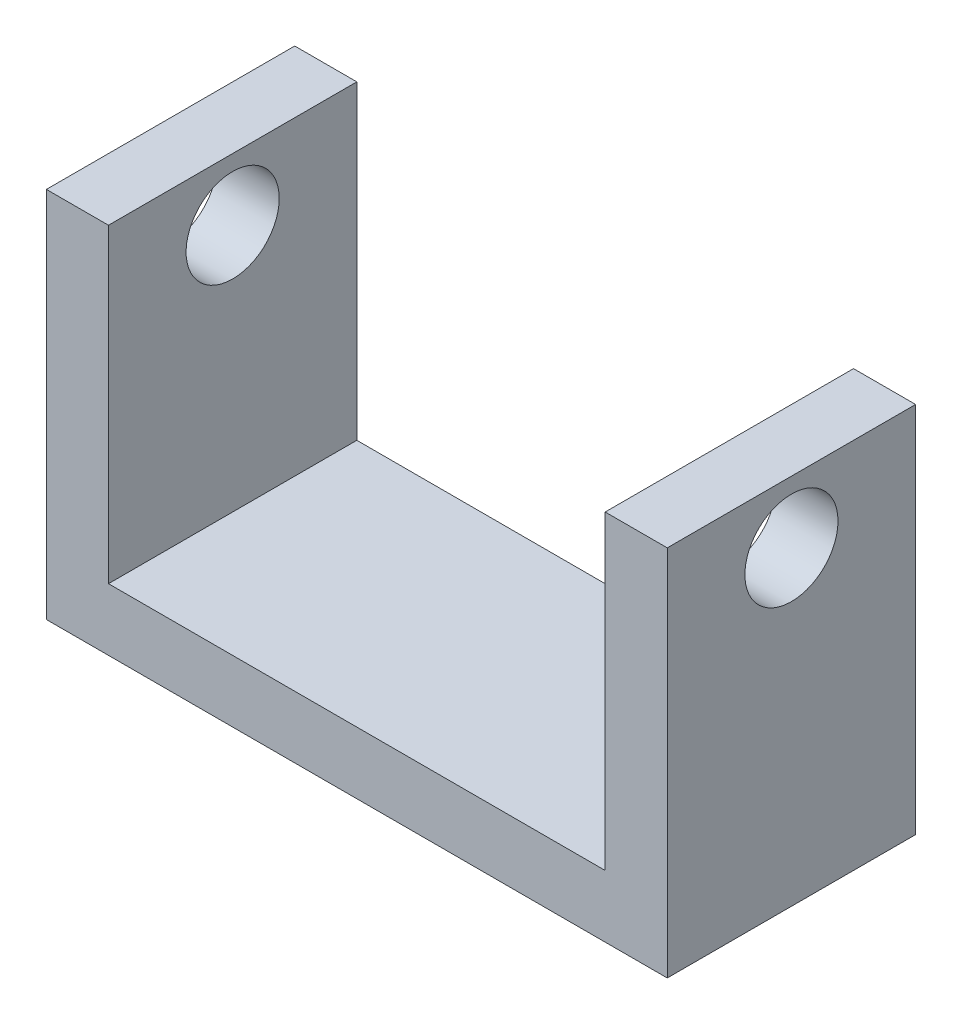
SolidWorks part; units mm, degrees
material "1060 Alloy"
ref_plane "Front Plane" through (0, 0, 0) normal (0, 0, 1) x (1, 0, 0)
ref_plane "Top Plane" through (0, 0, 0) normal (0, 1, 0) x (1, 0, 0)
ref_plane "Right Plane" through (0, 0, 0) normal (1, 0, 0) x (0, 0, -1)
sketch "Sketch1" plane through (0, 0, 0) normal (1, 0, 0) x (0, 0, -1)
  line L1 (0, 0) -> (12.7, 0)
  line L2 (0, 0) -> (0, 19.05)
  line L3 (0, 19.05) -> (12.7, 19.05)
  line L4 (12.7, 0) -> (12.7, 19.05)
  dimension "D1" = 12.7
  dimension "D2" = 19.05
extrude "Boss-Extrude1" add sketch "Sketch1" along normal blind 31.75
sketch "Sketch2" plane through (0, 0, 0) normal (0, 0, 1) x (1, 0, 0)
  line L0 (31.75, 19.05) -> (0, 19.05) construction
  line L1 (3.175, 19.05) -> (28.575, 19.05)
  line L2 (3.175, 19.05) -> (3.175, 3.175)
  line L3 (3.175, 3.175) -> (28.575, 3.175)
  line L4 (28.575, 19.05) -> (28.575, 3.175)
  line L5 (0, 19.05) -> (0, 0) construction
  line L6 (31.75, 19.05) -> (31.75, 0) construction
  line L7 (31.75, 0) -> (0, 0) construction
  dimension "D1" = 3.175
  dimension "D2" = 3.175
  dimension "D3" = 3.175
extrude "Cut-Extrude1" cut sketch "Sketch2" against normal up to next
hole_wizard "3/16 (0.1875) Diameter Hole1" positions "Sketch3" profile "Sketch4" hole size "3/16" standard "ANSI Inch" end condition through all
sketch "Sketch3" plane through (31.75, 0, 0) normal (1, 0, 0) x (0, 0, -1)
  line L0 (12.7, 19.05) -> (0, 19.05) construction
  point P0 (6.35, 15.875)
  point P7 (6.35, 19.05)
  dimension "D1" = 3.175
sketch "Sketch4" plane through (31.75, 15.875, -6.35) normal (0, 1, 0) x (0, 0, -1)
  line L0 (0, 0) -> (0, 31.75)
  line L1 (0, 31.75) -> (2.3812, 31.75)
  line L2 (2.3812, 31.75) -> (2.3812, 0)
  line L5 (2.3812, 0) -> (0, 0)
  line L11 (0, -6.35) -> (0, 107.95) construction
  dimension "Thru Hole Dia." = 4.7625
  dimension "Thru Hole Depth" = 31.75
